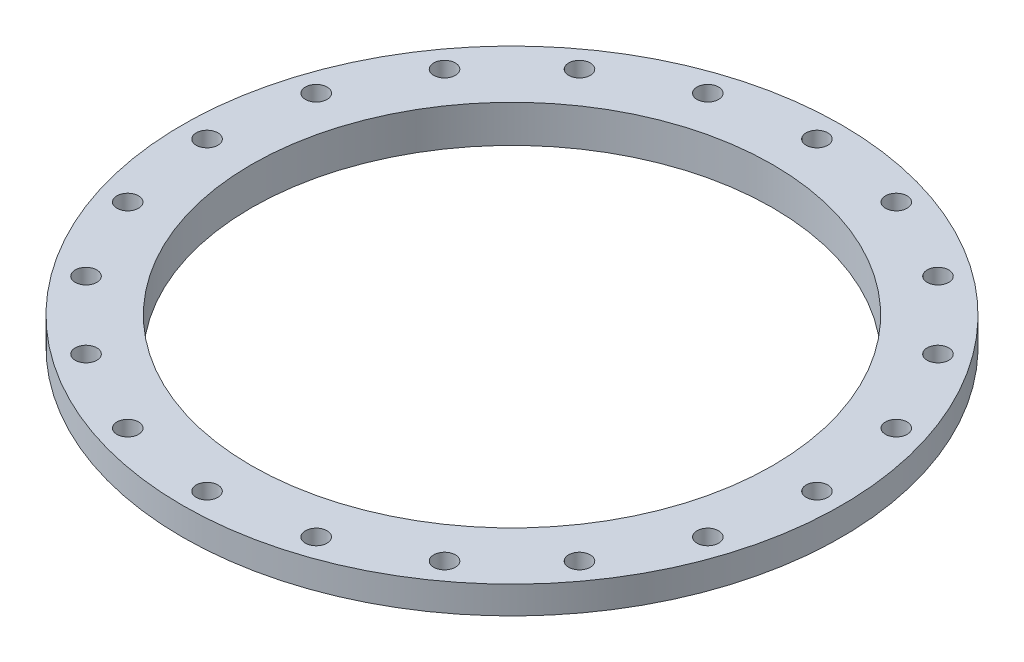
SolidWorks part; units mm, degrees
ref_plane "Front Plane" through (0, 0, 0) normal (0, 0, 1) x (1, 0, 0)
ref_plane "Top Plane" through (0, 0, 0) normal (0, 1, 0) x (1, 0, 0)
ref_plane "Right Plane" through (0, 0, 0) normal (1, 0, 0) x (0, 0, -1)
sketch "Sketch1" plane through (0, 0, 0) normal (1, 0, 0) x (0, 0, -1)
  line L0 (0, 1813.3166) -> (0, -1355.4542) construction
  line L1 (-335, 19) -> (-335, -9)
  line L2 (-335, -9) -> (-296.1397, -9)
  line L5 (-265, -19) -> (-265, 19)
  line L6 (-265, 19) -> (-335, 19)
  line L7 (-296.1397, -9) -> (-292.5, -19)
  line L8 (-292.5, -19) -> (-265, -19)
  line L10 (-310, 85.8484) -> (-310, -47.3009) construction
  point P7 (-265, 0)
  dimension "D1" = 530
  dimension "D2" = 670
  dimension "D3" = 28
  dimension "D4" = 10
  dimension "D5" = 585
  dimension "D6" = 310
  dimension "D7" = 110
revolve "Revolve1" add sketch "Sketch1" angle 360 about L0
sketch "Sketch2" plane through (0, -9, 0) normal (0, -1, 0) x (1, 0, 0)
  line L0 (0, 377.2661) -> (0, -198.7516) construction
  circle A0 centre (0, 310) radius 11
  circle A1 centre (95.7953, 294.8275) radius 11
  circle A2 centre (182.2134, 250.7953) radius 11
  circle A3 centre (250.7953, 182.2134) radius 11
  circle A4 centre (294.8275, 95.7953) radius 11
  circle A5 centre (310, 0) radius 11
  circle A6 centre (294.8275, -95.7953) radius 11
  circle A7 centre (250.7953, -182.2134) radius 11
  circle A8 centre (182.2134, -250.7953) radius 11
  circle A9 centre (95.7953, -294.8275) radius 11
  circle A10 centre (0, -310) radius 11
  circle A11 centre (-95.7953, -294.8275) radius 11
  circle A12 centre (-182.2134, -250.7953) radius 11
  circle A13 centre (-250.7953, -182.2134) radius 11
  circle A14 centre (-294.8275, -95.7953) radius 11
  circle A15 centre (-310, 0) radius 11
  circle A16 centre (-294.8275, 95.7953) radius 11
  circle A17 centre (-250.7953, 182.2134) radius 11
  circle A18 centre (-182.2134, 250.7953) radius 11
  circle A19 centre (-95.7953, 294.8275) radius 11
  circle A20 centre (0, 0) radius 310 construction
  point P45 (0, 0)
  dimension "D1" = 310
  dimension "D2" = 22
  dimension "D4" = 620
  dimension "D3" = 20
extrude "Cut-Extrude1" cut sketch "Sketch2" against normal through all both and the other way through all
